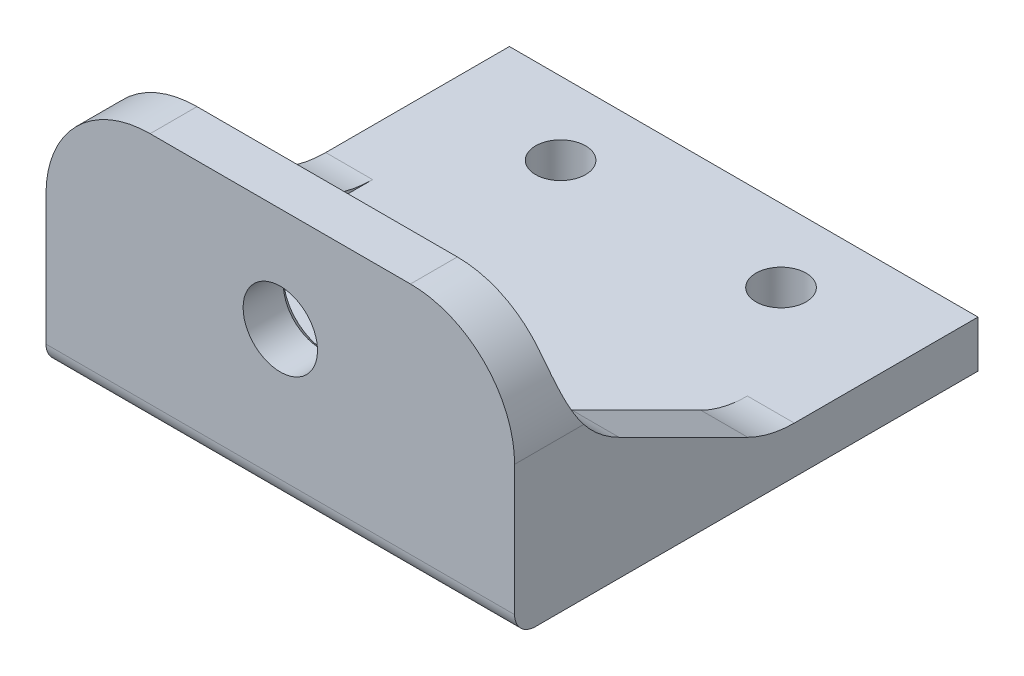
SolidWorks part; units mm, degrees
material "ABS PC"
ref_plane "Front Plane" through (0, 0, 0) normal (0, 0, 1) x (1, 0, 0)
ref_plane "Top Plane" through (0, 0, 0) normal (0, 1, 0) x (1, 0, 0)
ref_plane "Right Plane" through (0, 0, 0) normal (1, 0, 0) x (0, 0, -1)
sketch "Sketch1" plane through (0, 0, 0) normal (0, 1, 0) x (1, 0, 0)
  line L5 (-22.5, -77.5) -> (22.5, -77.5)
  line L6 (-22.5, -77.5) -> (-22.5, 0)
  line L8 (22.5, -77.5) -> (22.5, 0)
  line L9 (-22.5, -77.5) -> (22.5, 0) construction
  line L10 (-22.5, 0) -> (22.5, -77.5) construction
  arc A0 (22.5, 0) -> (-22.5, 0) centre (0, 0) ccw
  point P2 (0, -38.75)
  dimension "D1" = 45
  dimension "D2" = 100
  dimension "D3" = 45
extrude "Boss-Extrude1" add sketch "Sketch1" along normal blind 4.5
sketch "Sketch2" plane through (0, 4.5, 0) normal (0, 1, 0) x (1, 0, 0)
  line L0 (-6.697, 16.1679) -> (6.697, 16.1679) construction
  circle A0 centre (0, 0) radius 17.5 construction
  circle A1 centre (0, 0) radius 17.5 construction
  circle A2 centre (0, 0) radius 17.5 construction
  circle A3 centre (0, 0) radius 17.5 construction
  circle A4 centre (0, 0) radius 17.5 construction
  circle A5 centre (0, 0) radius 17.5 construction
  circle A6 centre (0, 0) radius 17.5 construction
  circle A7 centre (0, 0) radius 17.5 construction
  point P3 (-6.697, 16.1679)
  point P5 (-16.1679, -6.697)
  point P7 (6.697, 16.1679)
  point P9 (16.1679, 6.697)
  point P11 (16.1679, -6.697)
  point P13 (6.697, -16.1679)
  point P15 (-6.697, -16.1679)
  point P16 (0, 0)
  point P18 (-16.1679, 6.697)
  dimension "D1" = 35
  dimension "D2" = 8
hole_wizard "M5 Clearance Hole1" positions "Sketch3" profile "Sketch4" hole size "M5" standard "ANSI Metric" end condition through all
sketch "Sketch3" plane through (0, 4.5, 0) normal (0, 1, 0) x (1, 0, 0)
  point P0 (-6.697, -16.1679)
  point P3 (6.697, -16.1679)
  point P6 (6.697, 16.1679)
  point P15 (-6.697, 16.1679)
sketch "Sketch4" plane through (-6.697, 4.5, 16.1679) normal (1, 0, 0) x (0, 0, 1)
  line L0 (0, 0) -> (0, 4.5)
  line L1 (0, 4.5) -> (2.75, 4.5)
  line L2 (2.75, 4.5) -> (2.75, 0.025)
  line L3 (2.75, 0.025) -> (2.775, 0)
  line L5 (2.775, 0) -> (0, 0)
  line L6 (-2.75, 0.025) -> (-2.775, 0) construction
  line L11 (0, -6.35) -> (0, 107.95) construction
  dimension "Thru Hole Dia." = 5.5
  dimension "Thru Hole Depth" = 4.5
  dimension "Near C'Sink Dia." = 5.55
  dimension "Near C'Sink Angle" = 90
sketch "Sketch5" plane through (0, 4.5, 0) normal (0, 1, 0) x (1, 0, 0)
  circle A0 centre (0, 0) radius 12.5
  dimension "D1" = 25
extrude "Cut-Extrude1" cut sketch "Sketch5" against normal through all
sketch "Sketch6" [suppressed] plane through (0, 6.35, 0) normal (0, 1, 0) x (1, 0, 0)
  line L0 (-22.5, -77.5) -> (22.5, -77.5) construction
  circle A0 centre (0, -71) radius 3.3782
  dimension "D1" = 6.7564
  dimension "D2" = 6.5
sketch "Sketch7" [suppressed] plane through (0, 6.35, 0) normal (0, 1, 0) x (1, 0, 0)
  line L0 (12.5, -58.5) -> (-12.5, -58.5) construction
  line L1 (12.5, -63) -> (-12.5, -63)
  line L2 (12.5, -54) -> (-12.5, -54)
  line L3 (0, -71) -> (0, 0) construction
  line L4 (12.5, -42.5) -> (-12.5, -42.5) construction
  line L5 (12.5, -47) -> (-12.5, -47)
  line L6 (12.5, -38) -> (-12.5, -38)
  line L7 (12.5, -26.5) -> (-12.5, -26.5) construction
  line L8 (12.5, -31) -> (-12.5, -31)
  line L9 (12.5, -22) -> (-12.5, -22)
  arc A0 (12.5, -63) -> (12.5, -54) centre (12.5, -58.5) ccw
  arc A1 (-12.5, -54) -> (-12.5, -63) centre (-12.5, -58.5) ccw
  arc A2 (12.5, -47) -> (12.5, -38) centre (12.5, -42.5) ccw
  arc A3 (-12.5, -38) -> (-12.5, -47) centre (-12.5, -42.5) ccw
  arc A4 (12.5, -31) -> (12.5, -22) centre (12.5, -26.5) ccw
  arc A5 (-12.5, -22) -> (-12.5, -31) centre (-12.5, -26.5) ccw
  circle A6 centre (0, -71) radius 3.3782 construction
  point P2 (0, -58.5)
  point P15 (0, -42.5)
  point P22 (0, -26.5)
  point P28 (0, -63)
  dimension "D2" = 4.5
  dimension "D4" = 8
  dimension "D3" = 25
  dimension "D1" = 3
extrude "Cut-Extrude3" [suppressed] cut sketch "Sketch7" against normal through all
sketch "Sketch12" plane through (0, 0, 77.5) normal (0, 0, 1) x (1, 0, 0)
  line L0 (-22.5, 4.5) -> (22.5, 4.5) construction
  line L1 (22.5, 0) -> (-22.5, 0)
  line L2 (22.5, 0) -> (22.5, 24.5)
  line L3 (22.5, 24.5) -> (-22.5, 24.5)
  line L4 (-22.5, 0) -> (-22.5, 24.5)
  dimension "D1" = 20
extrude "Boss-Extrude2" add sketch "Sketch12" along normal blind 4.5
sketch "Sketch13" plane through (0, 0, 77.5) normal (0, 0, -1) x (-1, 0, 0)
  line L0 (22.5, 4.5) -> (-22.5, 4.5) construction
  point P0 (0, 14.5)
  dimension "D1" = 10
hole_wizard "1/4 Clearance Hole1" positions "Sketch16" profile "Sketch17" hole size "1/4" standard "ANSI Inch" end condition through all
sketch "Sketch16" plane through (0, 0, 77.5) normal (0, 0, -1) x (-1, 0, 0)
  point P0 (0, 14.5)
sketch "Sketch17" plane through (0, 14.5, 77.5) normal (1, 0, 0) x (0, 1, 0)
  line L0 (0, 0) -> (0, 4.5)
  line L1 (0, 4.5) -> (3.5712, 4.5)
  line L2 (3.5712, 4.5) -> (3.5712, 0.635)
  line L3 (3.5712, 0.635) -> (4.2062, 0)
  line L5 (4.2062, 0) -> (0, 0)
  line L6 (-3.5712, 0.635) -> (-4.2062, 0) construction
  line L11 (0, -6.35) -> (0, 107.95) construction
  dimension "Thru Hole Dia." = 7.1425
  dimension "Thru Hole Depth" = 4.5
  dimension "Near C'Sink Dia." = 8.4125
  dimension "Near C'Sink Angle" = 90
fillet "Fillet1" radius 10 2 edges at (-22.5, 24.5, 79.75) (22.5, 24.5, 79.75)
fillet "Fillet2" radius 2 2 edges at (0, 0, 82) (0, 4.5, 77.5)
ref_plane "Plane1" through (0, 0, -22.5) normal (0, 0, 1) x (1, 0, 0)
sketch "Sketch18" plane through (0, 0, -22.5) normal (0, 0, 1) x (1, 0, 0)
  line L1 (-32.4973, -4.485) -> (73.8257, -4.485)
  line L2 (-32.4973, -4.485) -> (-32.4973, 66.5178)
  line L3 (-32.4973, 66.5178) -> (73.8257, 66.5178)
  line L4 (73.8257, -4.485) -> (73.8257, 66.5178)
extrude "Cut-Extrude4" cut sketch "Sketch18" along normal blind 60
sketch "Sketch19" plane through (0, 0, 0) normal (0, -1, 0) x (1, 0, 0)
  line L0 (-10.5848, 44.5) -> (10.5848, 44.5) construction
  line L1 (22.5, 37.5) -> (-22.5, 37.5) construction
  point P2 (0, 44.5)
  point P5 (0, 37.5)
  dimension "D1" = 7
  dimension "D2" = 21.1696
hole_wizard "M4 Clearance Hole1" positions "Sketch20" profile "Sketch21" hole size "M4" standard "ANSI Metric" end condition through all
sketch "Sketch20" plane through (0, 0, 0) normal (0, -1, 0) x (-1, 0, 0)
  point P0 (10.5848, -44.5)
  point P3 (-10.5848, -44.5)
sketch "Sketch21" plane through (-10.5848, 0, 44.5) normal (1, 0, 0) x (0, 0, -1)
  line L0 (0, 0) -> (0, 24.5)
  line L1 (0, 24.5) -> (2.4, 24.5)
  line L2 (2.4, 24.5) -> (2.4, 0)
  line L5 (2.4, 0) -> (0, 0)
  line L11 (0, -6.35) -> (0, 107.95) construction
  dimension "Thru Hole Dia." = 4.8
  dimension "Thru Hole Depth" = 24.5
sketch "Sketch23" plane through (-22.5, 0, 0) normal (-1, 0, 0) x (0, 0, 1)
  line L0 (77.5, 14.5) -> (57.5, 4.5)
  line L1 (77.5, 14.5) -> (77.5, 6.5) construction
  line L2 (37.5, 4.5) -> (75.5, 4.5) construction
  line L3 (57.5, 4.5) -> (77.5, 4.5)
  line L4 (77.5, 4.5) -> (77.5, 14.5)
  dimension "D1" = 10
  dimension "D2" = 20
extrude "Boss-Extrude3" add sketch "Sketch23" against normal blind 4.5
fillet "Fillet3" radius 10 2 edges at (-20.25, 4.5, 57.5) (-20.25, 14.5, 77.5)
mirror "Mirror1" about plane through (0, 0, 0) normal (1, 0, 0) of "Boss-Extrude3", "Fillet3"
ref_plane "Plane2" through (0, 0, 112.75) normal (0, 0, 1) x (1, 0, 0)
sketch "Sketch24" plane through (0, 0, 112.75) normal (0, 0, 1) x (1, 0, 0)
  line L0 (0, 14.5) -> (0, 0) construction
  line L2 (22.5, 0) -> (-22.5, 0) construction
  line L3 (0, 0) -> (0, -1.8) construction
  point P0 (0, 14.5)
  point P1 (23.5362, 12.5561)
  dimension "D1" = 1.8
